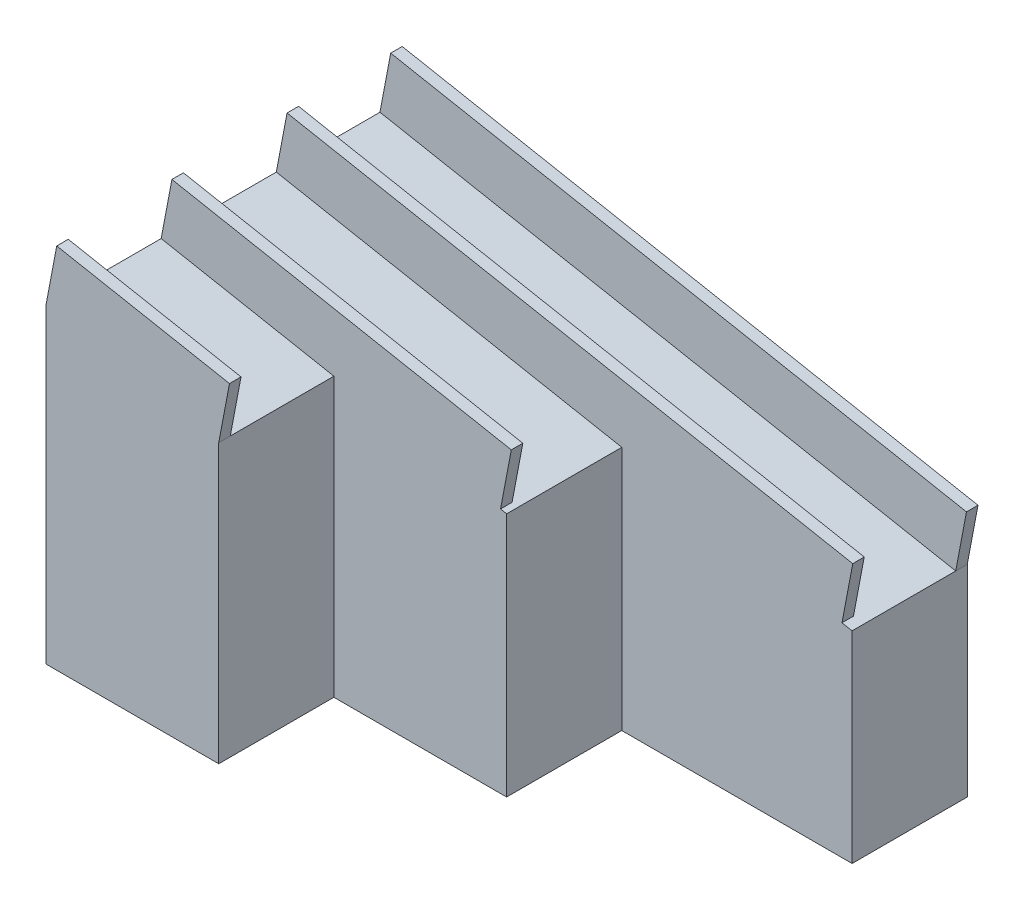
SolidWorks part; units mm, degrees
ref_plane "Front Plane" through (0, 0, 0) normal (0, 0, 1) x (1, 0, 0)
ref_plane "Top Plane" through (0, 0, 0) normal (0, 1, 0) x (1, 0, 0)
ref_plane "Right Plane" through (0, 0, 0) normal (1, 0, 0) x (0, 0, -1)
sketch "Sketch1" plane through (0, 0, 0) normal (0, 0, 1) x (1, 0, 0)
  line L0 (0, 0) -> (0, 54)
  line L1 (0, 54) -> (100, 35)
  line L2 (100, 35) -> (100, 0)
  line L3 (100, 0) -> (0, 0)
  dimension "D1" = 54
  dimension "D2" = 100
  dimension "30" = 35
extrude "Boss-Extrude1" add sketch "Sketch1" along normal blind 20
sketch "Sketch2" plane through (0, 0, 20) normal (0, 0, 1) x (1, 0, 0)
  line L0 (0, 54) -> (0, 0)
  line L1 (0, 0) -> (60, 0)
  line L2 (0, 0) -> (100, 0) construction
  line L3 (60, 0) -> (60, 42.6)
  line L4 (100, 35) -> (0, 54) construction
  line L5 (60, 42.6) -> (0, 54)
  dimension "D1" = 60
extrude "Boss-Extrude2" add sketch "Sketch2" along normal blind 20
sketch "Sketch3" plane through (0, 0, 40) normal (0, 0, 1) x (1, 0, 0)
  line L0 (0, 54) -> (0, 0)
  line L4 (0, 54) -> (30, 48.3)
  line L5 (60, 42.6) -> (0, 54) construction
  line L6 (30, 48.3) -> (30, 0)
  line L7 (0, 0) -> (60, 0) construction
  line L8 (30, 0) -> (0, 0)
  dimension "D1" = 30
extrude "Boss-Extrude3" add sketch "Sketch3" along normal blind 20
sketch "Sketch4" plane through (9.9025, 52.1185, 0) normal (0.1867, 0.9824, 0) x (0.9824, -0.1867, 0)
  line L0 (91.7093, -20) -> (91.7093, 0) construction
  line L1 (-10.0797, 0) -> (91.7093, 0)
  line L2 (-10.0797, 0) -> (-10.0797, -2)
  line L3 (-10.0797, -2) -> (91.7093, -2)
  line L4 (91.7093, 0) -> (91.7093, -2)
  line L5 (-10.0797, -60) -> (-10.0797, 0) construction
  line L6 (89.9203, -18) -> (-10.0797, -18)
  line L7 (89.9203, -18) -> (89.9203, -20)
  line L8 (89.9203, -20) -> (-10.0797, -20)
  line L9 (-10.0797, -18) -> (-10.0797, -20)
  line L11 (49.9203, -38) -> (-10.0797, -38)
  line L12 (49.9203, -38) -> (49.9203, -40)
  line L13 (49.9203, -40) -> (-10.0797, -40)
  line L14 (-10.0797, -38) -> (-10.0797, -40)
  line L15 (20.457, -60) -> (-10.0797, -60)
  line L16 (20.457, -60) -> (20.457, -58)
  line L17 (20.457, -58) -> (-10.0797, -58)
  line L18 (-10.0797, -60) -> (-10.0797, -58)
  line L24 (91.7093, -20) -> (50.9937, -20) construction
  line L25 (50.9937, -40) -> (20.457, -40) construction
  dimension "D1" = 2
  dimension "D2" = 2
  dimension "D3" = 2
  dimension "D4" = 2
  dimension "D5" = 60
  dimension "D6" = 100
  dimension "D7" = 2
  dimension "D8" = 2
extrude "Boss-Extrude4" add sketch "Sketch4" along normal blind 10
